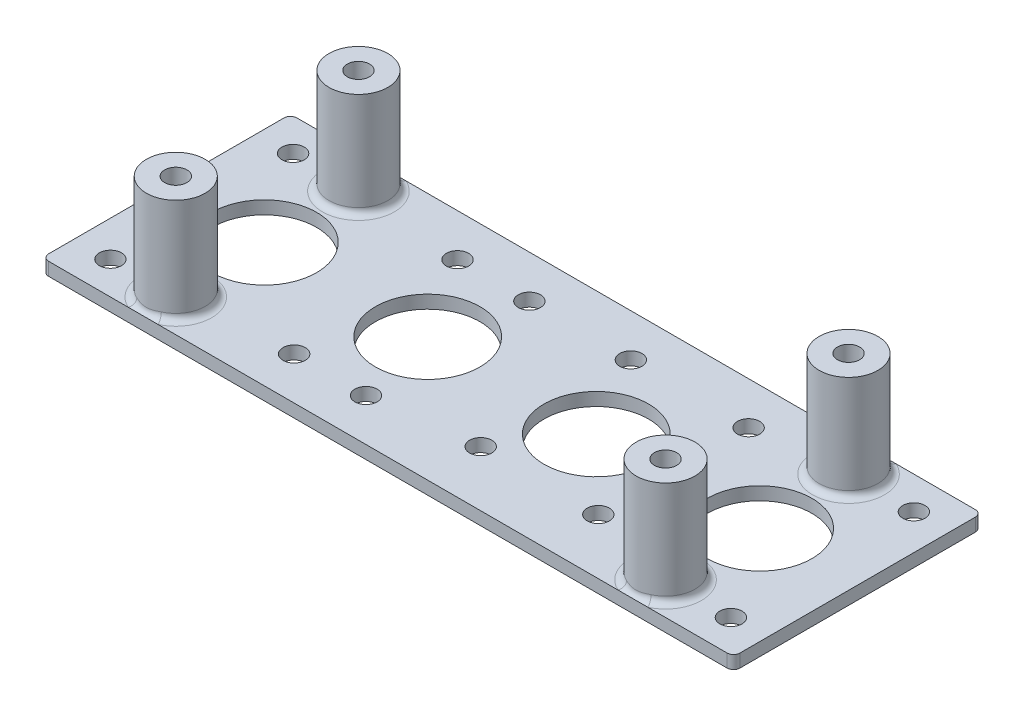
SolidWorks part; units mm, degrees
ref_plane "Front Plane" through (0, 0, 0) normal (0, 0, 1) x (1, 0, 0)
ref_plane "Top Plane" through (0, 0, 0) normal (0, 1, 0) x (1, 0, 0)
ref_plane "Right Plane" through (0, 0, 0) normal (1, 0, 0) x (0, 0, -1)
sketch "Sketch1" plane through (0, 0, 0) normal (0, 1, 0) x (1, 0, 0)
  line L1 (-52.9, 19) -> (52.9, 19)
  line L2 (-52.9, 19) -> (-52.9, -19)
  line L3 (-52.9, -19) -> (52.9, -19)
  line L4 (52.9, 19) -> (52.9, -19)
  circle A0 centre (-47.5, 14) radius 1.7
  circle A1 centre (-47.4521, -14) radius 1.7
  circle A2 centre (47.5, 14) radius 1.7
  circle A3 centre (47.5, -14) radius 1.7
  circle A4 centre (-20.8388, 12.5) radius 1.7
  circle A5 centre (-20.8388, -12.5) radius 1.7
  circle A6 centre (-9.8388, 12.5) radius 1.7
  circle A7 centre (-9.8388, -12.5) radius 1.7
  circle A8 centre (5.7083, 12.4823) radius 1.7
  circle A9 centre (5.7083, -10.5) radius 1.7
  circle A10 centre (23.7083, 12.5) radius 1.7
  circle A11 centre (23.7083, -10.5) radius 1.7
  circle A12 centre (-37.5, 14) radius 1.7
  circle A13 centre (-37.4521, -14) radius 1.7
  circle A14 centre (37.5, 14) radius 1.7
  circle A15 centre (37.5, -14) radius 1.7
  circle A16 centre (-37.9, 0) radius 8
  circle A17 centre (-12.9, 0) radius 8
  circle A19 centre (37.9, 0) radius 8
  circle A20 centre (12.9, 0) radius 8
  dimension "D3" = 28
  dimension "D4" = 95
  dimension "D5" = 105.8
  dimension "D7" = 11
  dimension "D10" = 6.5
  dimension "D13" = 10
  dimension "D18" = 75
  dimension "D19" = 52.9
  dimension "D25" = 15
  dimension "D24" = 15
  dimension "D26" = 25
  dimension "D1" = 5
  dimension "D2" = 5
  dimension "D6" = 5.4
  dimension "D8" = 25
  dimension "D9" = 6.5
  dimension "D11" = 23
  dimension "D12" = 18
  dimension "D14" = 10
  dimension "D15" = 10
  dimension "D16" = 10
  dimension "D17" = 28
  dimension "D20" = 19
  dimension "D21" = 0
  dimension "D22" = 25
  dimension "D23" = 11
  dimension "D27" = 25
extrude "Boss-Extrude3" add sketch "Sketch1" along normal blind 2
fillet "Fillet1" radius 1 4 edges at (52.9, 1, -19) (52.9, 1, 19) (-52.9, 1, -19) (-52.9, 1, 19)
sketch "Sketch4" plane through (0, 2, 0) normal (0, 1, 0) x (1, 0, 0)
  circle A0 centre (-37.5, 14) radius 4.5
  circle A1 centre (-37.4521, -14) radius 4.5
  circle A2 centre (37.5, 14) radius 4.5
  circle A3 centre (37.5, -14) radius 4.5
  circle A4 centre (-37.5, 14) radius 1.7
  circle A5 centre (-37.4521, -14) radius 1.7
  circle A6 centre (37.5, 14) radius 1.7
  circle A7 centre (37.5, -14) radius 1.7
extrude "Boss-Extrude4" add sketch "Sketch4" along normal blind 16
fillet "Fillet2" radius 1 4 edges at (37.5, 2, 18.5) (37.5, 2, -9.5) (-37.5, 2, -9.5) (-37.4521, 2, 18.5)
sketch "Sketch7" plane through (0, 0, 0) normal (0, -1, 0) x (1, 0, 0)
  line L31 (-39.4759, 10.5018) -> (-35.4345, 10.4982)
  line L32 (-35.4345, 10.4982) -> (-33.4107, 13.9964)
  line L33 (-33.4107, 13.9964) -> (-35.4283, 17.4982)
  line L34 (-35.4283, 17.4982) -> (-39.4698, 17.5018)
  line L35 (-39.4698, 17.5018) -> (-41.4936, 14.0036)
  line L36 (-41.4936, 14.0036) -> (-39.4759, 10.5018)
  line L37 (-39.5535, -17.4808) -> (-35.5123, -17.5188)
  line L38 (-35.5123, -17.5188) -> (-33.4587, -14.0379)
  line L39 (-33.4587, -14.0379) -> (-35.4465, -10.5191)
  line L40 (-35.4465, -10.5191) -> (-39.4877, -10.4811)
  line L41 (-39.4877, -10.4811) -> (-41.5413, -13.962)
  line L42 (-41.5413, -13.962) -> (-39.5535, -17.4808)
  line L49 (39.5571, 10.5213) -> (41.5412, 14.0422)
  line L50 (41.5412, 14.0422) -> (39.4841, 17.5209)
  line L51 (39.4841, 17.5209) -> (35.4429, 17.4788)
  line L52 (35.4429, 17.4788) -> (33.4588, 13.9579)
  line L53 (33.4588, 13.9579) -> (35.5159, 10.4792)
  line L54 (35.5159, 10.4792) -> (39.5571, 10.5213)
  line L55 (41.5415, -14) -> (39.5207, -10.5)
  line L56 (39.5207, -10.5) -> (35.4793, -10.5)
  line L57 (35.4793, -10.5) -> (33.4585, -14)
  line L58 (33.4585, -14) -> (35.4793, -17.5)
  line L59 (35.4793, -17.5) -> (39.5207, -17.5)
  line L60 (39.5207, -17.5) -> (41.5415, -14)
  circle A0 centre (37.5, 14) radius 3.5 construction
  circle A1 centre (37.5, -14) radius 3.5 construction
  circle A2 centre (-37.4521, 14) radius 3.5 construction
  circle A3 centre (-37.5, -14) radius 3.5 construction
extrude "Cut-Extrude1" cut sketch "Sketch7" against normal blind 2
